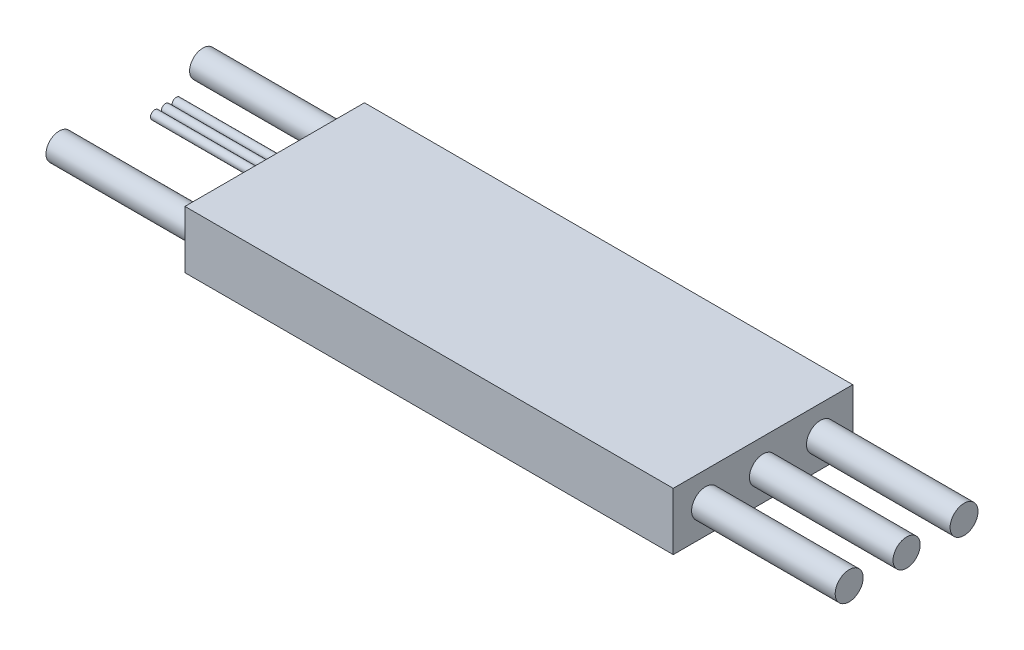
SolidWorks part; units mm, degrees
ref_plane "Plan de face" through (0, 0, 0) normal (0, 0, 1) x (1, 0, 0)
ref_plane "Plan de dessus" through (0, 0, 0) normal (0, 1, 0) x (1, 0, 0)
ref_plane "Plan de droite" through (0, 0, 0) normal (1, 0, 0) x (0, 0, -1)
sketch "Esquisse1" plane through (0, 0, 0) normal (0, 1, 0) x (1, 0, 0)
  line L1 (-34, 12.5) -> (34, 12.5)
  line L2 (-34, 12.5) -> (-34, -12.5)
  line L3 (-34, -12.5) -> (34, -12.5)
  line L4 (34, 12.5) -> (34, -12.5)
  point P4 (0, 12.5)
  point P6 (-34, 0)
  dimension "D1" = 68
  dimension "D2" = 25
extrude "Boss.-Extru.1" add sketch "Esquisse1" along normal blind 8
sketch "Esquisse2" plane through (-34, 0, 0) normal (-1, 0, 0) x (0, 0, 1)
  line L0 (0, 0) -> (0, 8) construction
  line L1 (-12.5, 0) -> (12.5, 0) construction
  line L2 (-12.5, 8) -> (12.5, 8) construction
  circle A0 centre (-10, 4) radius 1.85
  circle A1 centre (10, 4) radius 1.85
  circle A2 centre (-6.3025, 1.1625) radius 0.6
  circle A3 centre (-4.8025, 1.1625) radius 0.6
  circle A4 centre (-3.3025, 1.1625) radius 0.6
  point P11 (0, 4)
  dimension "D1" = 3.7
  dimension "D3" = 1.2
  dimension "D2" = 20
  dimension "D4" = 3
extrude "Boss.-Extru.2" add sketch "Esquisse2" along normal blind 20
sketch "Esquisse3" plane through (34, 0, 0) normal (1, 0, 0) x (0, 0, -1)
  line L0 (0, 0) -> (0, 8) construction
  line L1 (-12.5, 8) -> (12.5, 8) construction
  circle A0 centre (-8, 4) radius 1.9457
  circle A1 centre (0, 4) radius 1.8914
  circle A2 centre (8, 4) radius 1.9457
  dimension "D1" = 16
extrude "Boss.-Extru.3" add sketch "Esquisse3" along normal blind 20
